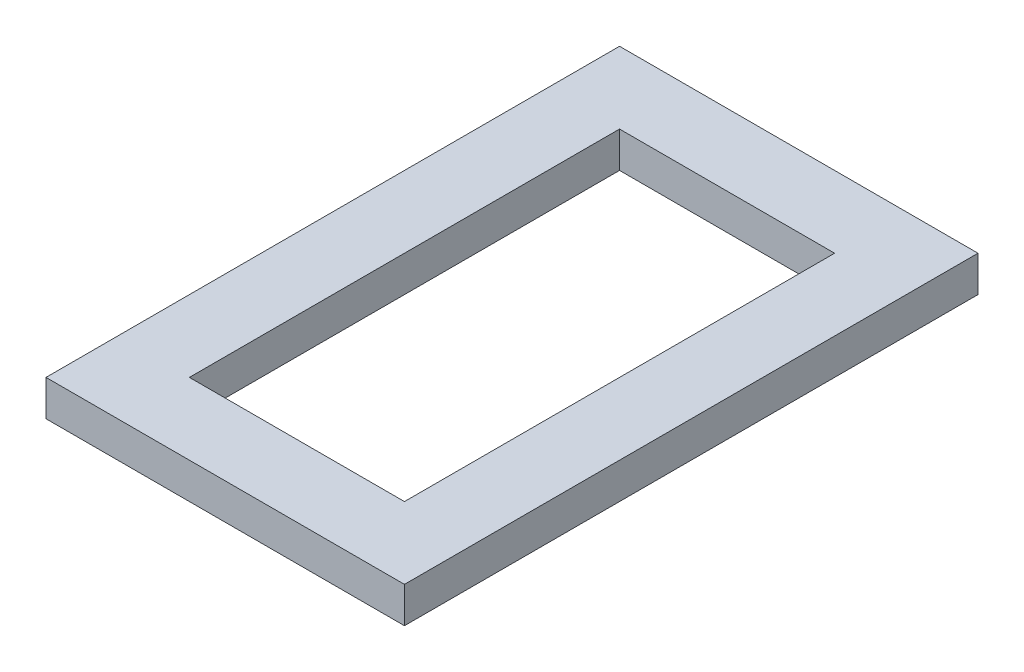
SolidWorks part; units mm, degrees
ref_plane "Front Plane" through (0, 0, 0) normal (0, 0, 1) x (1, 0, 0)
ref_plane "Top Plane" through (0, 0, 0) normal (0, 1, 0) x (1, 0, 0)
ref_plane "Right Plane" through (0, 0, 0) normal (1, 0, 0) x (0, 0, -1)
sketch "Sketch1" plane through (0, 0, 0) normal (0, 1, 0) x (1, 0, 0)
  line L1 (0, 0) -> (-63.5, 0)
  line L2 (0, 0) -> (0, 101.6)
  line L3 (0, 101.6) -> (-63.5, 101.6)
  line L4 (-63.5, 0) -> (-63.5, 101.6)
  dimension "D1" = 63.5
  dimension "D2" = 101.6
extrude "Boss-Extrude1" add sketch "Sketch1" along normal blind 6.35 contours L4 L3 L2 L1
sketch "Sketch2" plane through (0, 6.35, 0) normal (0, 1, 0) x (1, 0, 0)
  line L1 (-50.8, 12.7) -> (-12.7, 12.7)
  line L2 (-50.8, 12.7) -> (-50.8, 88.9)
  line L3 (-50.8, 88.9) -> (-12.7, 88.9)
  line L4 (-12.7, 12.7) -> (-12.7, 88.9)
  dimension "D1" = 76.2
  dimension "D2" = 38.1
extrude "Cut-Extrude1" cut sketch "Sketch2" against normal through all
